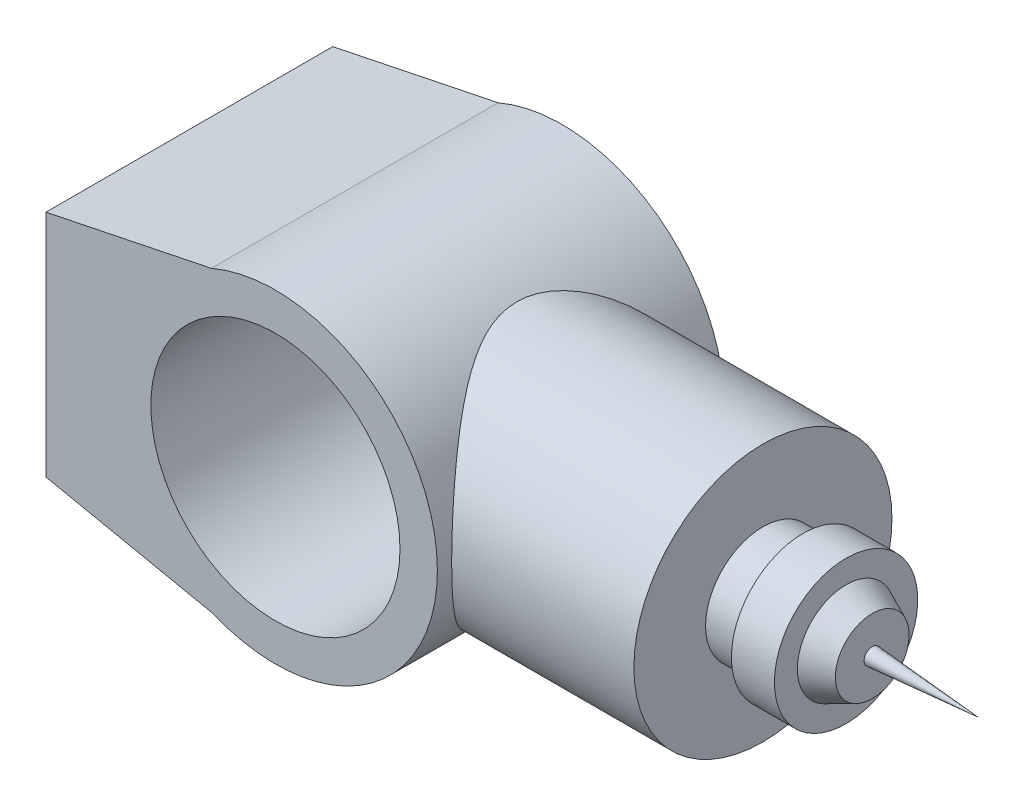
SolidWorks part; units mm, degrees
ref_plane "Front Plane" through (0, 0, 0) normal (0, 0, 1) x (1, 0, 0)
ref_plane "Top Plane" through (0, 0, 0) normal (0, 1, 0) x (1, 0, 0)
ref_plane "Right Plane" through (0, 0, 0) normal (1, 0, 0) x (0, 0, -1)
sketch "Sketch2" plane through (0, 0, 0) normal (0, 0, 1) x (1, 0, 0)
  line L0 (-80, -40) -> (-80, 40)
  line L2 (-80, 40) -> (-22.3464, 51.8715)
  line L4 (-80, -40) -> (-21.8292, -52.0912)
  circle A0 centre (0, 0) radius 43.4447
  arc A1 (-21.8292, -52.0912) -> (-22.3464, 51.8715) centre (0, 0) ccw
  point P7 (-80, 0)
  dimension "D1" = 80
  dimension "D2" = 80
extrude "Boss-Extrude1" add sketch "Sketch2" along normal mid plane 100
ref_plane "Plane1" through (120, 0, 0) normal (1, 0, 0) x (0, 0, -1)
sketch "Sketch3" plane through (120, 0, 0) normal (1, 0, 0) x (0, 0, -1)
  circle A0 centre (0, 0) radius 45
extrude "Boss-Extrude2" add sketch "Sketch3" against normal up to next
sketch "Sketch4" plane through (0, 0, 0) normal (0, 0, 1) x (1, 0, 0)
  line L0 (0, 0) -> (195.0462, 0) construction
  line L1 (120, 0) -> (120, -20)
  line L2 (120, -55) -> (120, 55) construction
  line L3 (120, -20) -> (134, -20)
  line L4 (134, -20) -> (134, -25)
  line L5 (134, -25) -> (149, -25)
  line L6 (149, -25) -> (149, -16.983)
  line L7 (149, -16.983) -> (158.1089, -12.8566)
  line L8 (158.1089, -12.8566) -> (158.1089, -2.8373)
  line L9 (158.1089, -2.8373) -> (195, 0)
  line L10 (195, 0) -> (120, 0)
  dimension "D1" = 20
  dimension "D2" = 14
  dimension "D3" = 5
  dimension "D4" = 15
  dimension "D5" = 10
  dimension "D6" = 37
  dimension "D7" = 75
revolve "Revolve1" add sketch "Sketch4" angle 360 about L0
